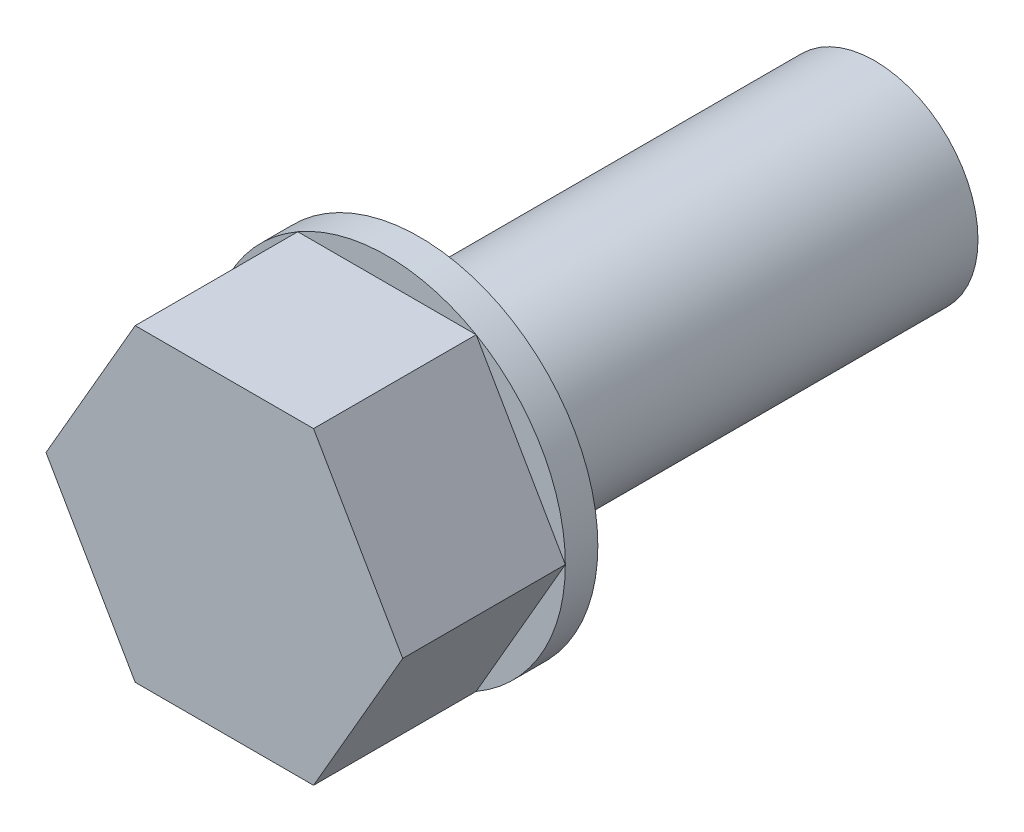
SolidWorks part; units mm, degrees
material "AISI 4340 Acero normalizado"
ref_plane "Alzado" through (0, 0, 0) normal (0, 0, 1) x (1, 0, 0)
ref_plane "Planta" through (0, 0, 0) normal (0, 1, 0) x (1, 0, 0)
ref_plane "Vista lateral" through (0, 0, 0) normal (1, 0, 0) x (0, 0, -1)
sketch "Croquis1" plane through (0, 0, 0) normal (0, 0, 1) x (1, 0, 0)
  circle A0 centre (0, 0) radius 6.35
extrude "Saliente-Extruir1" add sketch "Croquis1" along normal blind 30
sketch "Croquis2" plane through (0, 0, 30) normal (0, 0, 1) x (1, 0, 0)
  line L1 (10.9697, 0) -> (5.4848, 9.5)
  line L2 (5.4848, 9.5) -> (-5.4848, 9.5)
  line L3 (-5.4848, 9.5) -> (-10.9697, 0)
  line L4 (-10.9697, 0) -> (-5.4848, -9.5)
  line L5 (-5.4848, -9.5) -> (5.4848, -9.5)
  line L6 (5.4848, -9.5) -> (10.9697, 0)
  circle A0 centre (0, 0) radius 9.5 construction
  dimension "D1" = 19
extrude "Saliente-Extruir2" add sketch "Croquis2" along normal blind 10
sketch "Croquis3" plane through (0, 0, 30) normal (0, 0, -1) x (-1, 0, 0)
  circle A0 centre (0, 0) radius 10.9697
extrude "Saliente-Extruir3" add sketch "Croquis3" along normal blind 2
